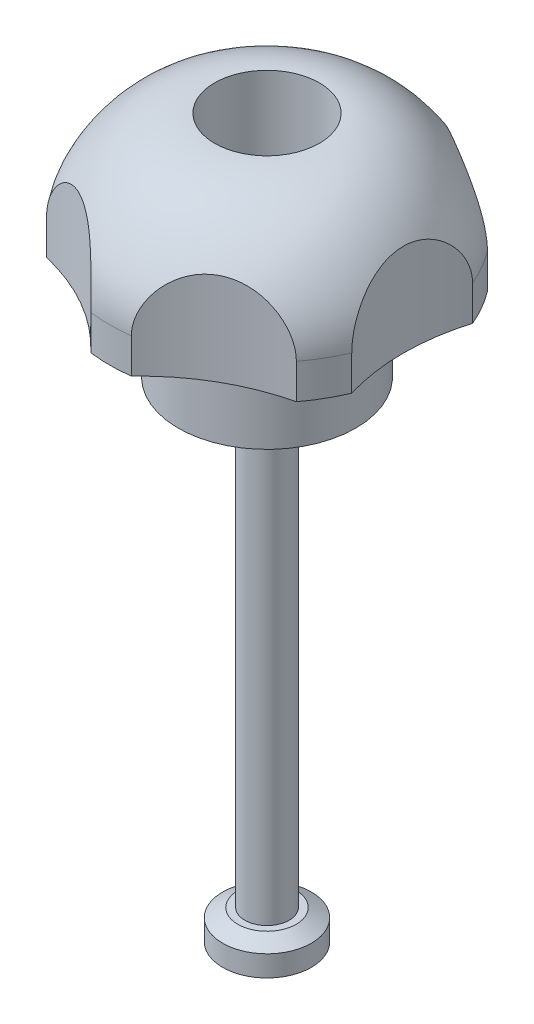
SolidWorks part; units mm, degrees
ref_plane "Alzado" through (0, 0, 0) normal (0, 0, 1) x (1, 0, 0)
ref_plane "Planta" through (0, 0, 0) normal (0, 1, 0) x (1, 0, 0)
ref_plane "Vista lateral" through (0, 0, 0) normal (1, 0, 0) x (0, 0, -1)
sketch "Croquis2" plane through (0, 0, 0) normal (0, 0, 1) x (1, 0, 0)
  line L0 (3.175, 70) -> (12.7, 70)
  line L2 (0, 0) -> (0, 90)
  line L3 (12.7, 70) -> (12.7, 87.7)
  line L4 (3.175, 4.2557) -> (3.175, 70)
  line L5 (7.5, 90) -> (0, 90)
  line L6 (13.4838, 87.7) -> (-49986.5162, 87.7) construction
  line L7 (3.175, 4.2557) -> (4.175, 4.2557)
  line L8 (18.5027, 82.7) -> (22.5, 82.7)
  line L9 (22.5, 82.7) -> (22.5, 87.7)
  line L10 (0, 150) -> (0, 50150) construction
  line L11 (-3.9035, 102.7) -> (49996.0965, 102.7) construction
  line L12 (18.5027, 104.297) -> (18.5027, 50104.297) construction
  line L13 (7.5, 102.7) -> (7.5, 90)
  line L14 (4.175, 4.2557) -> (6.35, 3)
  line L15 (6.35, 3) -> (6.35, 0)
  line L16 (6.35, 0) -> (0, 0)
  spline S0 degree 2 poles (12.7, 87.7) (18.5027, 87.7) (18.5027, 82.7) knots 0 0 0 1 1 1
  spline S1 degree 3 poles (7.5, 102.7) (13.0427, 102.7) (19.452, 97.8108) (22.5, 90.3806) (22.5, 87.7) knots 0 0 0 0 0.655381 1 1 1 1
  point P13 (19.9354, 85.2955)
  dimension "D5" = 3.9973
  dimension "D4" = 20
  dimension "D2" = 3.175
  dimension "D3" = 20
  dimension "D6" = 22.5
  dimension "D7" = 7.5
  dimension "D8" = 12.7
  dimension "D9" = 15
  dimension "D10" = 12.7
  dimension "D11" = 15
  dimension "D12" = 3
  dimension "D13" = 1
  dimension "D14" = 60
  dimension "D15" = 6.35
  dimension "D16" = 90
  dimension "D17" = 12.5
  dimension "D18" = 2.5
  dimension "D19" = 17
  dimension "D20" = 6.5
revolve "Revolución1" add sketch "Croquis2" angle 360 about L2
sketch "Croquis3" plane through (0, 82.7, 0) normal (0, -1, 0) x (1, 0, 0)
  arc A0 (20.7727, 8.6454) -> (20.7727, -8.6454) centre (49.5, 0) ccw
  circle A1 centre (0, 0) radius 22.5 construction
  arc A2 (20.7727, 8.6454) -> (20.7727, -8.6454) centre (0, 0) cw
  arc A3 (17.8735, -13.667) -> (2.8992, -22.3124) centre (24.75, -42.8683) ccw
  arc A4 (17.8735, -13.667) -> (2.8992, -22.3124) centre (0, 0) cw
  arc A5 (-2.8992, -22.3124) -> (-17.8735, -13.667) centre (-24.75, -42.8683) ccw
  arc A6 (-2.8992, -22.3124) -> (-17.8735, -13.667) centre (0, 0) cw
  arc A7 (-20.7727, -8.6454) -> (-20.7727, 8.6454) centre (-49.5, 0) ccw
  arc A8 (-20.7727, -8.6454) -> (-20.7727, 8.6454) centre (0, 0) cw
  arc A9 (-17.8735, 13.667) -> (-2.8992, 22.3124) centre (-24.75, 42.8683) ccw
  arc A10 (-17.8735, 13.667) -> (-2.8992, 22.3124) centre (0, 0) cw
  arc A11 (2.8992, 22.3124) -> (17.8735, 13.667) centre (24.75, 42.8683) ccw
  arc A12 (2.8992, 22.3124) -> (17.8735, 13.667) centre (0, 0) cw
  point P5 (19.5, 0)
  point P10 (22.5, 0)
  point P15 (11.25, -19.4856)
  point P19 (-11.25, -19.4856)
  point P23 (-22.5, 0)
  point P27 (-11.25, 19.4856)
  point P31 (11.25, 19.4856)
  point P32 (0, 0)
  dimension "D1" = 30
  dimension "D3" = 6
  dimension "D2" = 3
extrude "Cortar-Extruir1" cut sketch "Croquis3" against normal through all
